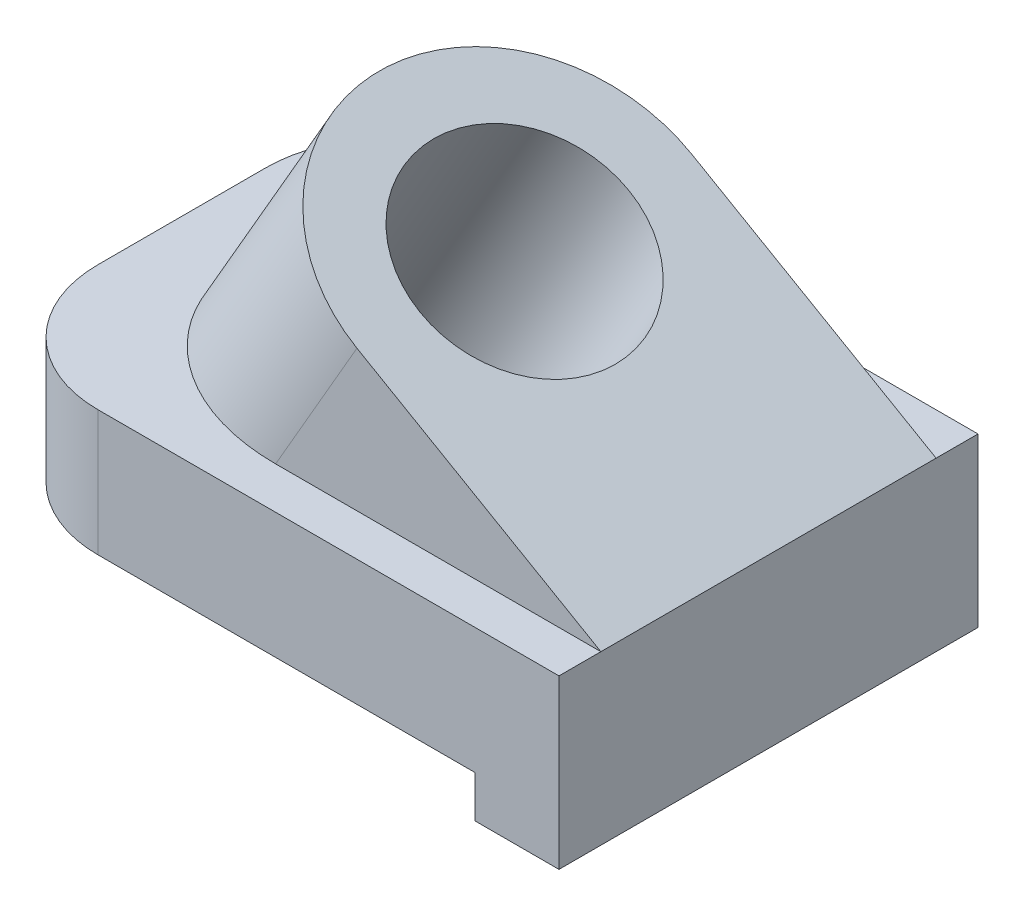
SolidWorks part; units mm, degrees
ref_plane "Front Plane" through (0, 0, 0) normal (0, 0, 1) x (1, 0, 0)
ref_plane "Top Plane" through (0, 0, 0) normal (0, 1, 0) x (1, 0, 0)
ref_plane "Right Plane" through (0, 0, 0) normal (1, 0, 0) x (0, 0, -1)
sketch "Sketch1" plane through (0, 0, 0) normal (0, 0, 1) x (1, 0, 0)
  line L0 (60, 0) -> (70, 0)
  line L1 (70, 0) -> (70, 20)
  line L2 (70, 20) -> (0, 20)
  line L3 (0, 20) -> (0, 5)
  line L4 (0, 5) -> (60, 5)
  line L5 (60, 5) -> (60, 0)
  dimension "D1" = 10
  dimension "D2" = 15
  dimension "D3" = 5
  dimension "D4" = 70
extrude "Boss-Extrude1" add sketch "Sketch1" along normal mid plane 50
fillet "Fillet1" radius 15 2 edges at (0, 12.5, -25) (0, 12.5, 25)
ref_plane "Plane1" through (26.1603, 45.3109, 0) normal (0.5, 0.866, 0) x (0, 0, -1)
sketch "Sketch2" plane through (26.1603, 45.3109, 0) normal (0.5, 0.866, 0) x (0, 0, -1)
  line L0 (-20, -50.6218) -> (20, -50.6218)
  line L1 (-25, -50.6218) -> (25, -50.6218) construction
  line L2 (20, -50.6218) -> (20, -17.0111)
  line L3 (-20, -17.0111) -> (-20, -50.6218)
  arc A0 (20, -17.0111) -> (-20, -17.0111) centre (0, -17.0111) ccw
  point P7 (0, -50.6218)
  dimension "D1" = 40
extrude "Boss-Extrude2" add sketch "Sketch2" against normal up to surface (19.4052 mm away)
sketch "Sketch3" plane through (26.1603, 45.3109, 0) normal (0.5, 0.866, 0) x (0, 0, -1)
  circle A0 centre (0, -17.0111) radius 12.5
  dimension "D1" = 25
extrude "Cut-Extrude1" cut sketch "Sketch3" against normal through all
